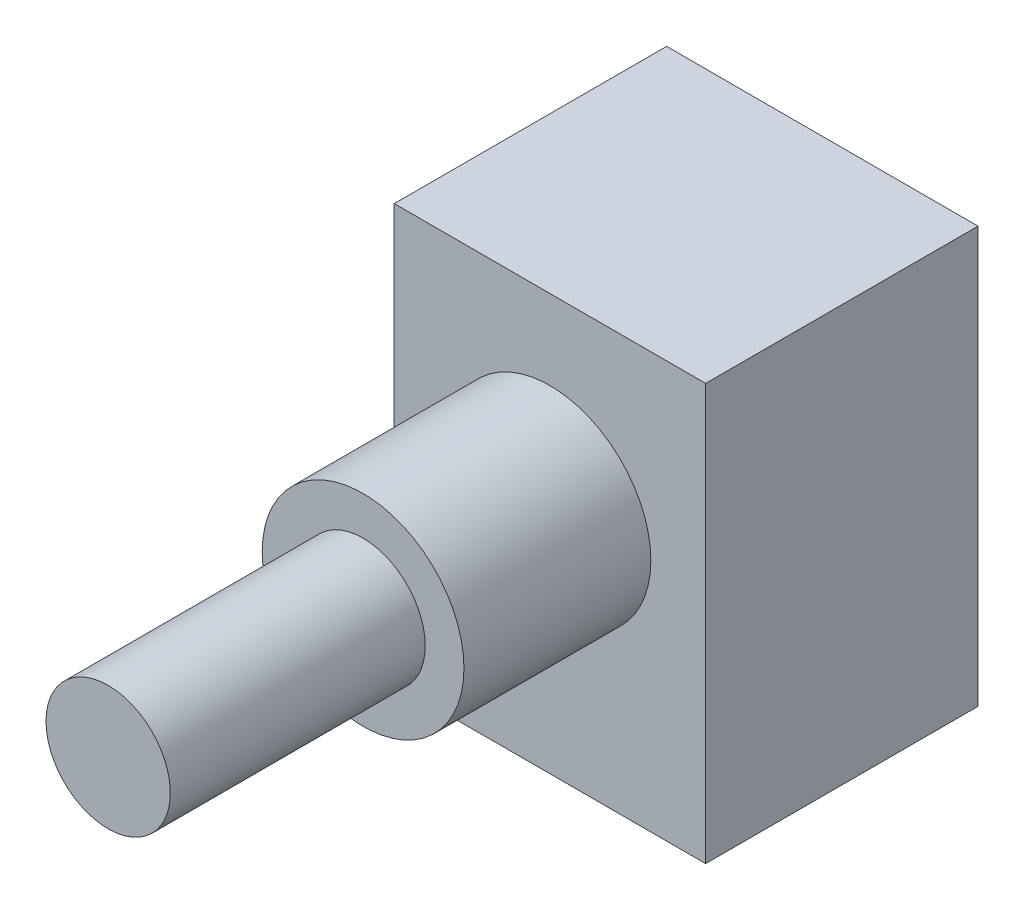
SolidWorks part; units mm, degrees
ref_plane "Front Plane" through (0, 0, 0) normal (0, 0, 1) x (1, 0, 0)
ref_plane "Top Plane" through (0, 0, 0) normal (0, 1, 0) x (1, 0, 0)
ref_plane "Right Plane" through (0, 0, 0) normal (1, 0, 0) x (0, 0, -1)
sketch "Sketch2" plane through (0, 0, 0) normal (0, 0, 1) x (1, 0, 0)
  line L1 (0, 0) -> (15.88, 0)
  line L2 (0, 0) -> (0, 21.21)
  line L3 (0, 21.21) -> (15.88, 21.21)
  line L4 (15.88, 0) -> (15.88, 21.21)
  dimension "D1" = 15.88
  dimension "D2" = 21.21
extrude "Boss-Extrude1" add sketch "Sketch2" along normal blind 13.89
sketch "Sketch3" plane through (0, 0, 13.89) normal (0, 0, 1) x (1, 0, 0)
  line L0 (0, 0) -> (15.88, 0) construction
  line L1 (0, 21.21) -> (0, 0) construction
  circle A0 centre (7.94, 12) radius 5.145
  dimension "D1" = 10.29
  dimension "D2" = 12
  dimension "D3" = 7.94
extrude "Boss-Extrude2" add sketch "Sketch3" along normal blind 9.53
sketch "Sketch4" plane through (0, 0, 23.42) normal (0, 0, 1) x (1, 0, 0)
  circle A1 centre (7.94, 12) radius 3.17
  dimension "D1" = 6.34
extrude "Boss-Extrude3" add sketch "Sketch4" along normal offset from surface (13 mm away) 22.53 up to face at (13.085, 12, 13.89) offset beyond the face yes
